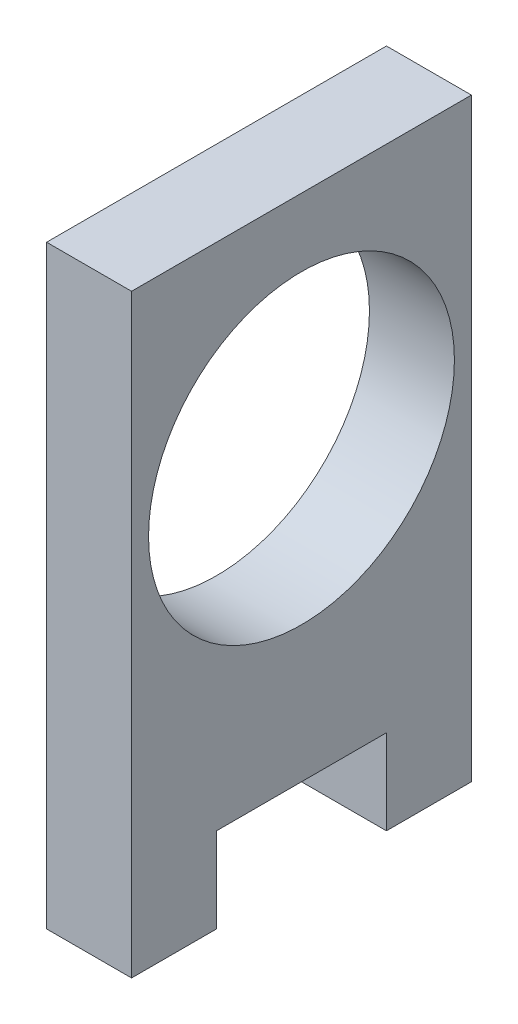
SolidWorks part; units mm, degrees
ref_plane "Front Plane" through (0, 0, 0) normal (0, 0, 1) x (1, 0, 0)
ref_plane "Top Plane" through (0, 0, 0) normal (0, 1, 0) x (1, 0, 0)
ref_plane "Right Plane" through (0, 0, 0) normal (1, 0, 0) x (0, 0, -1)
sketch "Sketch1" plane through (0, 0, 0) normal (1, 0, 0) x (0, 0, -1)
  line L0 (12.7, 38.1) -> (12.7, 0) construction
  line L1 (0, 0) -> (25.4, 0)
  line L2 (0, 0) -> (0, 38.1)
  line L3 (0, 38.1) -> (25.4, 38.1)
  line L4 (25.4, 0) -> (25.4, 38.1)
  line L5 (25.4, 0) -> (19.05, 0)
  line L6 (25.4, 0) -> (25.4, -6.35)
  line L7 (25.4, -6.35) -> (19.05, -6.35)
  line L8 (19.05, 0) -> (19.05, -6.35)
  line L9 (6.35, 0) -> (6.35, -6.35)
  line L10 (0, -6.35) -> (6.35, -6.35)
  line L11 (0, 0) -> (0, -6.35)
  line L12 (6.35, 0) -> (19.05, 0)
  line L13 (12.7, 38.1) -> (12.7, 33.02)
  circle A0 centre (12.7, 21.59) radius 11.43
  dimension "D1" = 6.35
  dimension "D2" = 6.35
  dimension "D3" = 12.7
extrude "Boss-Extrude1" add sketch "Sketch1" along normal blind 6.35 contours L1 L8 L7 L6 | L3 L0 A0 L12 L1 L4 | L0 L3 L2 L1 A0 | L1 L11 L10 L9
